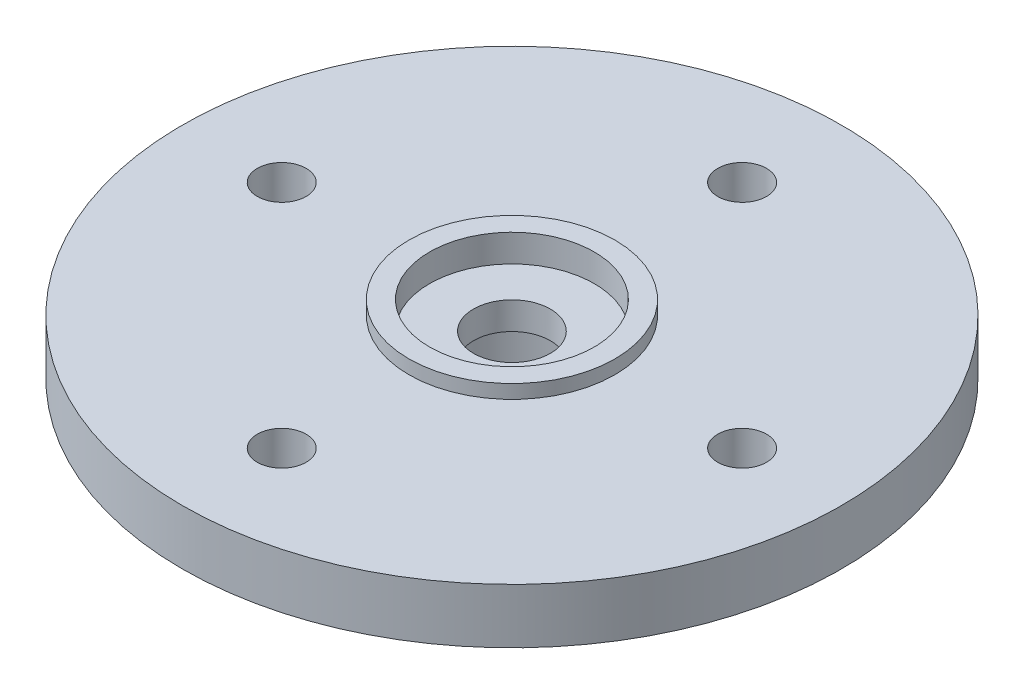
SolidWorks part; units mm, degrees
material "1060 Alloy"
ref_plane "Front Plane" through (0, 0, 0) normal (0, 0, 1) x (1, 0, 0)
ref_plane "Top Plane" through (0, 0, 0) normal (0, 1, 0) x (1, 0, 0)
ref_plane "Right Plane" through (0, 0, 0) normal (1, 0, 0) x (0, 0, -1)
sketch "Sketch1" plane through (0, 0, 0) normal (0, 0, 1) x (1, 0, 0)
  line L0 (0, 0) -> (0, -4.5) construction
  line L1 (0, -55) -> (0, 55) construction
  line L2 (55, 0) -> (-55, 0) construction
  line L3 (-12, 0) -> (-3.75, 0)
  line L4 (-12, 0) -> (-12, -2)
  line L5 (-12, -2) -> (-4.5, -2)
  line L6 (-1.4, 0.5) -> (-1.4, -4.5)
  line L8 (-4.5, -2) -> (-4.5, -4.5)
  line L9 (-4.5, -4.5) -> (-1.4, -4.5)
  line L10 (-3.75, 0.5) -> (-1.4, 0.5)
  line L11 (-3.75, 0.5) -> (-3.75, 0)
  dimension "D1" = 9
  dimension "D2" = 2.5
  dimension "D3" = 4.5
  dimension "D4" = 24
  dimension "D5" = 2.8
  dimension "D6" = 7.5
  dimension "D7" = 5
revolve "Revolve1" add sketch "Sketch1" angle 360 about L0
hole_wizard "#2-56 Tapped Hole1" positions "Sketch3" profile "Sketch2" tap size "#2-56" standard "ANSI Inch" end condition up to next
sketch "Sketch3" plane through (0, 0, 0) normal (0, 1, 0) x (-1, 0, 0)
  circle A0 centre (0, 0) radius 8.382 construction
  point P0 (0, -8.382)
  point P1 (8.382, 0)
  point P3 (-8.382, 0)
  point P5 (0, 8.382)
  dimension "D1" = 16.764
sketch "Sketch2" plane through (0, 0, -8.382) normal (1, 0, 0) x (0, 0, 1)
  line L0 (0, 0) -> (0, 2)
  line L1 (0, 2) -> (0.889, 2)
  line L2 (0.889, 2) -> (0.889, 0)
  line L5 (0.889, 0) -> (0, 0)
  line L11 (0, -6.35) -> (0, 107.95) construction
  dimension "Thru Tap Drill Dia." = 1.778
  dimension "Thru Tap Drill Depth" = 2
cosmetic thread "Hole Thread1" parameters "D2"=2.1844
cosmetic thread "Hole Thread2" parameters "D2"=2.1844
cosmetic thread "Hole Thread3" parameters "D2"=2.1844
cosmetic thread "Hole Thread4" parameters "D2"=2.1844
sketch "Sketch4" plane through (0, 0.5, 0) normal (0, 1, 0) x (-1, 0, 0)
  circle A0 centre (0, 0) radius 3
  dimension "D1" = 6
extrude "Cut-Extrude1" cut sketch "Sketch4" against normal blind 1
sketch "Sketch5" plane through (0, -4.5, 0) normal (0, -1, 0) x (1, 0, 0)
  circle A0 centre (0, 0) radius 3
  dimension "D1" = 6
extrude "Cut-Extrude2" cut sketch "Sketch5" against normal blind 3
